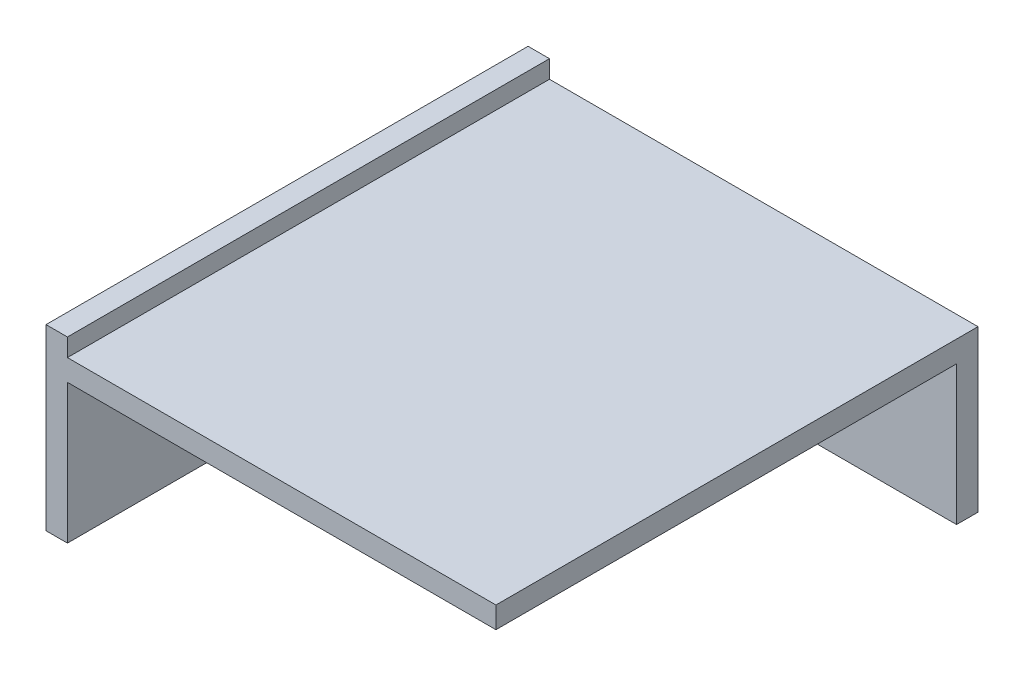
SolidWorks part; units mm, degrees
ref_plane "前视基准面" through (0, 0, 0) normal (0, 0, 1) x (1, 0, 0)
ref_plane "上视基准面" through (0, 0, 0) normal (0, 1, 0) x (1, 0, 0)
ref_plane "右视基准面" through (0, 0, 0) normal (1, 0, 0) x (0, 0, -1)
sketch "草图1" plane through (0, 0, 0) normal (0, 1, 0) x (1, 0, 0)
  line L1 (0, 0) -> (240, 0)
  line L2 (0, 0) -> (0, 270)
  line L3 (0, 270) -> (240, 270)
  line L4 (240, 0) -> (240, 270)
  dimension "D1" = 240
  dimension "D2" = 270
extrude "凸台-拉伸1" add sketch "草图1" along normal blind 12
sketch "草图2" plane through (0, 0, 0) normal (-1, 0, 0) x (0, 0, 1)
  line L0 (-270, 12) -> (0, 12) construction
  line L1 (-270, 22) -> (0, 22)
  line L2 (-270, 22) -> (-270, -78)
  line L3 (-270, -78) -> (0, -78)
  line L4 (0, 22) -> (0, -78)
  line L5 (0, 12) -> (0, 0) construction
  line L7 (-270, 12) -> (-270, 0) construction
  dimension "D1" = 10
  dimension "D2" = 100
extrude "凸台-拉伸2" add sketch "草图2" along normal blind 12
sketch "草图3" plane through (0, 0, 0) normal (1, 0, 0) x (0, 0, -1)
  line L0 (270, 0) -> (0, 0) construction
  line L1 (270, -78) -> (258, -78)
  line L2 (270, -78) -> (270, 0)
  line L3 (270, 0) -> (258, 0)
  line L4 (258, -78) -> (258, 0)
  dimension "D1" = 12
extrude "凸台-拉伸3" add sketch "草图3" along normal blind 240
